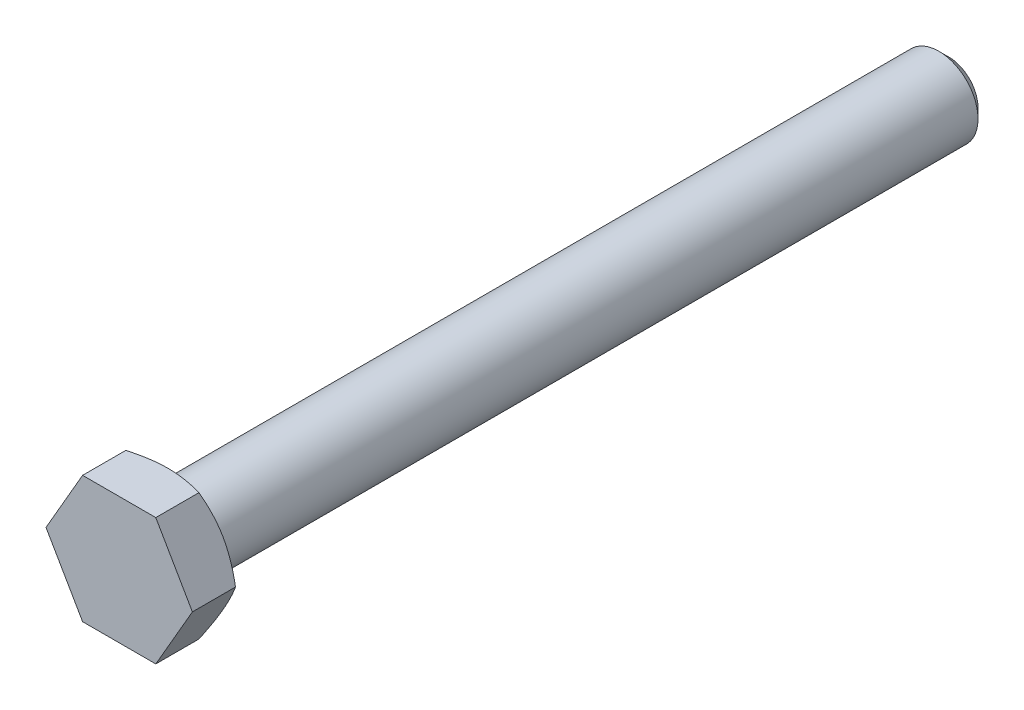
SolidWorks part; units mm, degrees
ref_plane "Płaszczyzna przednia" through (0, 0, 0) normal (0, 0, 1) x (1, 0, 0)
ref_plane "Płaszczyzna górna" through (0, 0, 0) normal (0, 1, 0) x (1, 0, 0)
ref_plane "Płaszczyzna prawa" through (0, 0, 0) normal (1, 0, 0) x (0, 0, -1)
sketch "Szkic1" plane through (0, 0, 0) normal (0, 0, 1) x (1, 0, 0)
  line L1 (3.75, 6.4952) -> (-3.75, 6.4952)
  line L2 (-3.75, 6.4952) -> (-7.5, 0)
  line L3 (-7.5, 0) -> (-3.75, -6.4952)
  line L4 (-3.75, -6.4952) -> (3.75, -6.4952)
  line L5 (3.75, -6.4952) -> (7.5, 0)
  line L6 (7.5, 0) -> (3.75, 6.4952)
  circle A0 centre (0, 0) radius 6.4952 construction
  dimension "D1" = 15
extrude "Dodanie-wyciągnięcie2" add sketch "Szkic1" along normal blind 5 contours L1 L2 L3 L4 L5 L6
sketch "Szkic3" plane through (0, 0, 0) normal (0, 0, 1) x (1, 0, 0)
  line L0 (3.75, 6.4952) -> (-3.75, 6.4952) construction
  circle A0 centre (0, 0) radius 6.4952
extrude "Wytnij-wyciągnięcie2" cut sketch "Szkic3" along normal blind 10 draft 60 flip side to cut
sketch "Szkic4" plane through (0, 0, 0) normal (0, 0, 1) x (1, 0, 0)
  circle A0 centre (0, 0) radius 4
  dimension "D1" = 8
extrude "Dodanie-wyciągnięcie3" add sketch "Szkic4" against normal blind 80 contours A0
fillet "Zaokrąglenie1" radius 1 1 edges at (4, 0, 0)
chamfer "Sfazowanie1" distance 1 angle 45 1 edges at (4, 0, -80)
